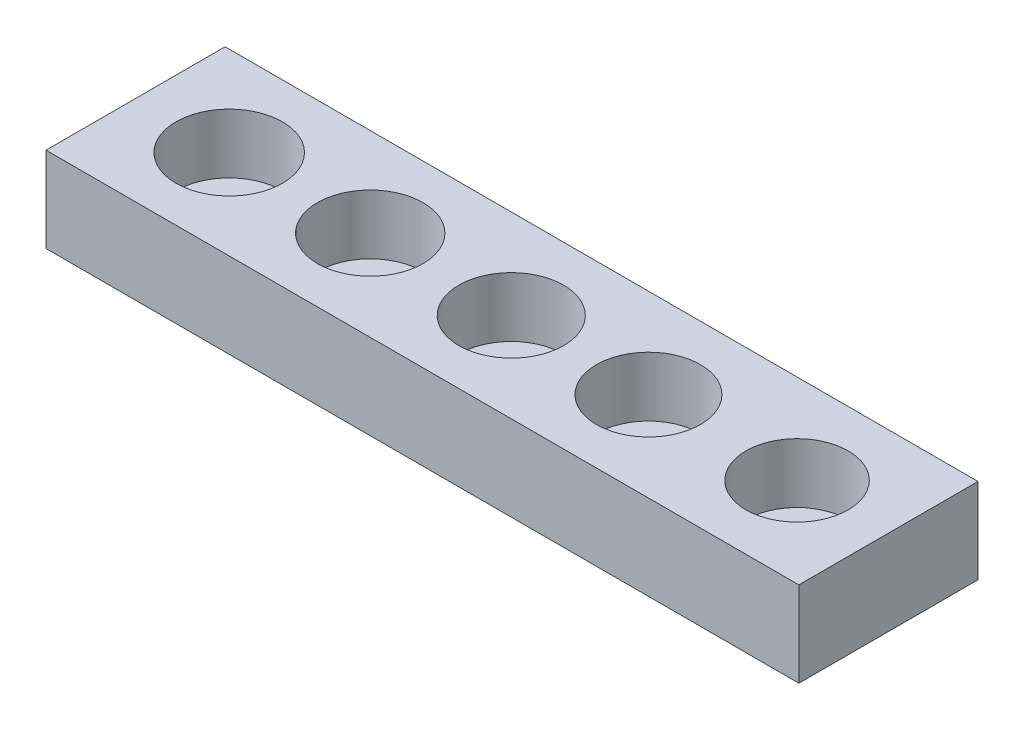
SolidWorks part; units mm, degrees
ref_plane "Front Plane" through (0, 0, 0) normal (0, 0, 1) x (1, 0, 0)
ref_plane "Top Plane" through (0, 0, 0) normal (0, 1, 0) x (1, 0, 0)
ref_plane "Right Plane" through (0, 0, 0) normal (1, 0, 0) x (0, 0, -1)
sketch "Sketch4" plane through (0, 0, 0) normal (0, 1, 0) x (1, 0, 0)
  line L1 (-22.0919, -5.2558) -> (22.0919, -5.2558)
  line L2 (-22.0919, -5.2558) -> (-22.0919, 5.2558)
  line L3 (-22.0919, 5.2558) -> (22.0919, 5.2558)
  line L4 (22.0919, -5.2558) -> (22.0919, 5.2558)
  line L5 (-22.0919, -5.2558) -> (22.0919, 5.2558) construction
  line L6 (-22.0919, 5.2558) -> (22.0919, -5.2558) construction
  point P0 (0, 0)
extrude "Boss-Extrude1" add sketch "Sketch4" along normal blind 5 contours L2 L1 L4 L3
sketch "Sketch5" plane through (0, 5, 0) normal (0, 1, 0) x (1, 0, 0)
  line L0 (-22.0919, 0) -> (22.0919, 0) construction
  line L1 (-22.0919, -5.2558) -> (-22.0919, 5.2558) construction
  line L2 (22.0919, -5.2558) -> (22.0919, 5.2558) construction
  circle A0 centre (-16.5954, 0) radius 3.125
  circle A1 centre (-8.3637, 0.0445) radius 3.1
  circle A2 centre (-0.0445, 0) radius 3.075
  circle A3 centre (8.0078, 0) radius 3.05
  circle A4 centre (16.7275, 0) radius 3
extrude "Cut-Extrude1" cut sketch "Sketch5" against normal blind 3.5
